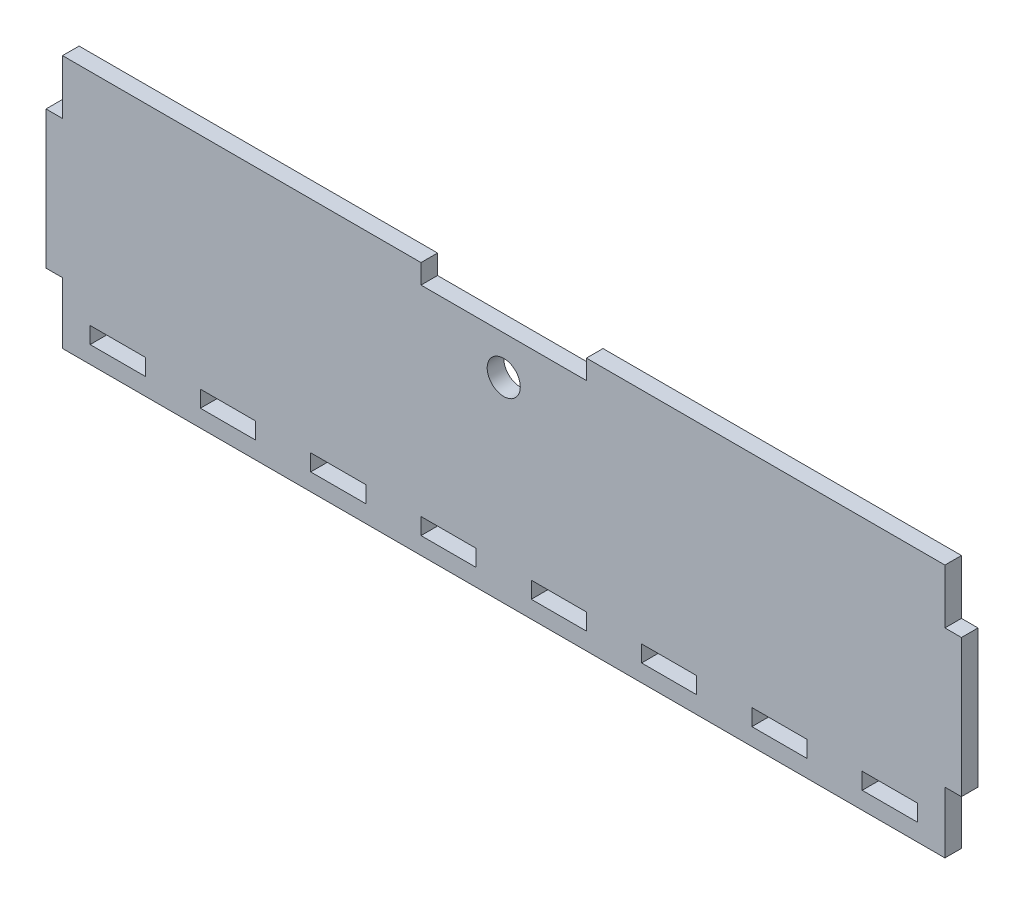
SolidWorks part; units mm, degrees
ref_plane "Front Plane" through (0, 0, 0) normal (0, 0, 1) x (1, 0, 0)
ref_plane "Top Plane" through (0, 0, 0) normal (0, 1, 0) x (1, 0, 0)
ref_plane "Right Plane" through (0, 0, 0) normal (1, 0, 0) x (0, 0, -1)
sketch "Sketch1" plane through (0, 0, 0) normal (0, 0, 1) x (1, 0, 0)
  line L0 (-6.3615, -18.573) -> (-6.3615, -21.573)
  line L1 (-31.3615, 21.3052) -> (33.6385, 21.3052)
  line L2 (-31.3615, 21.3052) -> (-31.3615, 11.427)
  line L3 (-31.3615, -24.6948) -> (128.6385, -24.6948)
  line L4 (128.6385, 21.3052) -> (128.6385, 11.427)
  line L5 (-26.3615, -18.573) -> (-16.3615, -18.573)
  line L6 (-26.3615, -18.573) -> (-26.3615, -21.573)
  line L7 (-26.3615, -21.573) -> (-16.3615, -21.573)
  line L8 (-16.3615, -18.573) -> (-16.3615, -21.573)
  line L9 (-6.3615, -18.573) -> (3.6385, -18.573)
  line L10 (3.6385, -18.573) -> (3.6385, -21.573)
  line L11 (-6.3615, -21.573) -> (3.6385, -21.573)
  line L12 (13.6385, -18.573) -> (13.6385, -21.573)
  line L13 (13.6385, -18.573) -> (23.6385, -18.573)
  line L14 (23.6385, -18.573) -> (23.6385, -21.573)
  line L15 (13.6385, -21.573) -> (23.6385, -21.573)
  line L16 (33.6385, -18.573) -> (33.6385, -21.573)
  line L17 (33.6385, -18.573) -> (43.6385, -18.573)
  line L18 (43.6385, -18.573) -> (43.6385, -21.573)
  line L19 (33.6385, -21.573) -> (43.6385, -21.573)
  line L20 (53.6385, -18.573) -> (53.6385, -21.573)
  line L21 (53.6385, -18.573) -> (63.6385, -18.573)
  line L22 (63.6385, -18.573) -> (63.6385, -21.573)
  line L23 (53.6385, -21.573) -> (63.6385, -21.573)
  line L24 (73.6385, -18.573) -> (73.6385, -21.573)
  line L25 (73.6385, -18.573) -> (83.6385, -18.573)
  line L26 (83.6385, -18.573) -> (83.6385, -21.573)
  line L27 (73.6385, -21.573) -> (83.6385, -21.573)
  line L28 (93.6385, -18.573) -> (93.6385, -21.573)
  line L29 (93.6385, -18.573) -> (103.6385, -18.573)
  line L30 (103.6385, -18.573) -> (103.6385, -21.573)
  line L31 (93.6385, -21.573) -> (103.6385, -21.573)
  line L32 (113.6385, -18.573) -> (113.6385, -21.573)
  line L33 (113.6385, -18.573) -> (123.6385, -18.573)
  line L34 (123.6385, -18.573) -> (123.6385, -21.573)
  line L35 (113.6385, -21.573) -> (123.6385, -21.573)
  line L36 (-31.3615, -13.573) -> (-31.3615, -24.6948)
  line L37 (-31.3615, 11.427) -> (-34.3615, 11.427)
  line L39 (-31.3615, -13.573) -> (-34.3615, -13.573)
  line L40 (-34.3615, 11.427) -> (-34.3615, -13.573)
  line L41 (128.6385, 11.427) -> (131.6385, 11.427)
  line L43 (128.6385, -13.573) -> (131.6385, -13.573)
  line L44 (131.6385, 11.427) -> (131.6385, -13.573)
  line L45 (128.6385, -13.573) -> (128.6385, -24.6948)
  line L46 (63.6385, 21.3052) -> (128.6385, 21.3052)
  line L48 (33.6385, 21.3052) -> (33.6385, 17.7692)
  line L49 (33.6385, 17.7692) -> (63.6385, 17.7692)
  line L50 (63.6385, 21.3052) -> (63.6385, 17.7692)
  circle A0 centre (48.6385, 10.7692) radius 3
  dimension "D15" = 7
  dimension "D1" = 46
  dimension "D2" = 160
  dimension "D3" = 5
  dimension "3" = 3.1219
  dimension "D4" = 3
  dimension "D5" = 8
  dimension "10" = 10
  dimension "D6" = 5
  dimension "D7" = 25
  dimension "D8" = 3
  dimension "D9" = 5
  dimension "D10" = 25
  dimension "D11" = 3
  dimension "D12" = 5
  dimension "D13" = 30
  dimension "D14" = 65
  dimension "D16" = 15
extrude "Boss-Extrude1" add sketch "Sketch1" along normal blind 3 contours L20 L23 L22 L21 | L16 L19 L18 L17 | L0 L11 L10 L9 | A0 | L1 L48 L49 L50 L46 L4 L41 L44 L43 L45 L3 L36 L39 L40 L37 L2 | L33 L34 L35 L32 | L31 L30 L29 L28 | L27 L26 L25 L24 | L15 L14 L13 L12 | L5 L8 L7 L6
